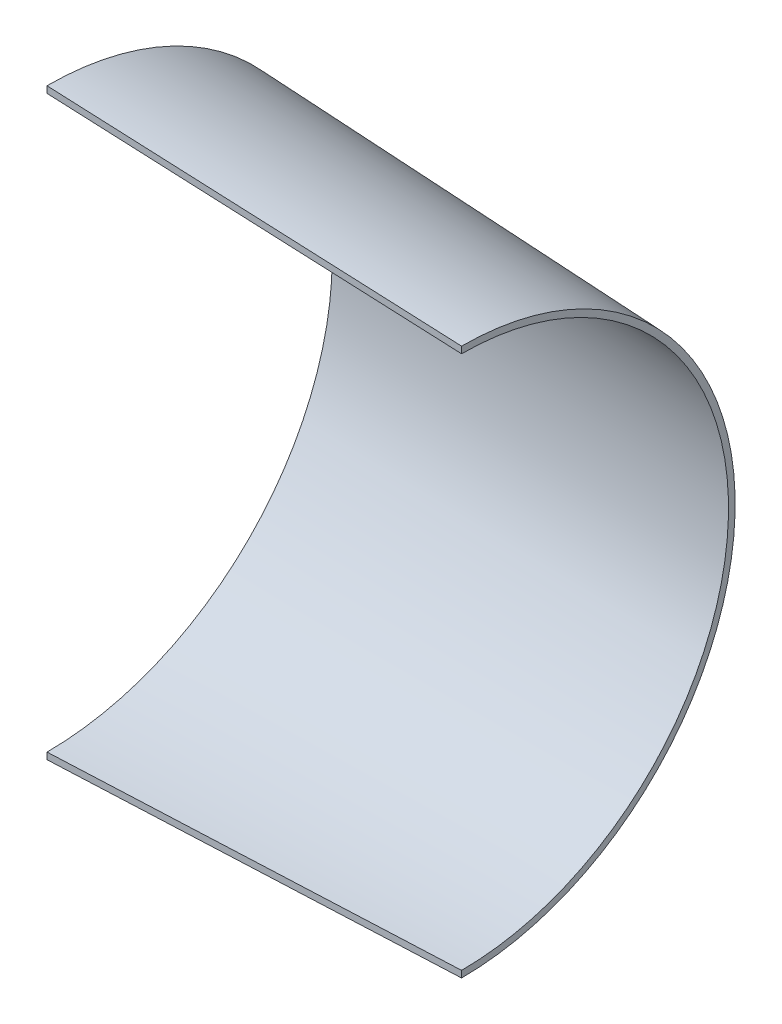
SolidWorks part; units mm, degrees
ref_plane "Front Plane" through (0, 0, 0) normal (0, 0, 1) x (1, 0, 0)
ref_plane "Top Plane" through (0, 0, 0) normal (0, 1, 0) x (1, 0, 0)
ref_plane "Right Plane" through (0, 0, 0) normal (1, 0, 0) x (0, 0, -1)
sketch "Sketch1" plane through (0, 0, 0) normal (0, 0, 1) x (1, 0, 0)
  line L0 (0, 0) -> (4000, 0) construction
  line L1 (700, -1720) -> (700, -1760)
  line L2 (700, -1760) -> (3200, -1650)
  line L3 (3200, -1650) -> (3200, -1610)
  line L4 (3200, -1610) -> (700, -1720)
revolve "Revolve1" add sketch "Sketch1" angle 180 about L0
